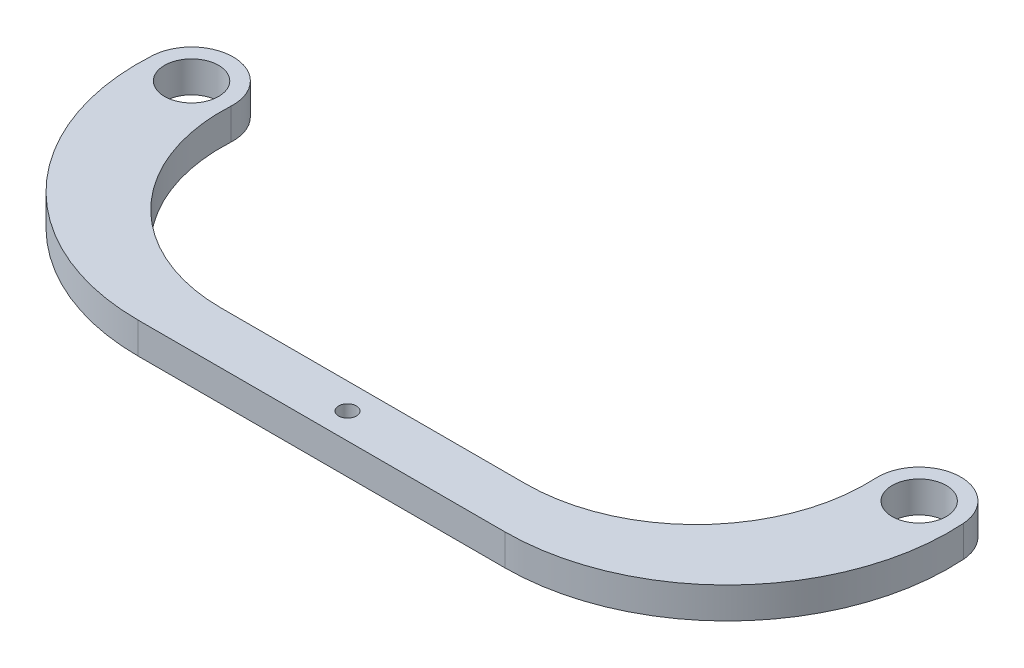
SolidWorks part; units mm, degrees
ref_plane "前视基准面" through (0, 0, 0) normal (0, 0, 1) x (1, 0, 0)
ref_plane "上视基准面" through (0, 0, 0) normal (0, 1, 0) x (1, 0, 0)
ref_plane "右视基准面" through (0, 0, 0) normal (1, 0, 0) x (0, 0, -1)
other "Configuration Table"
sketch "草图1" plane through (0, 0, 0) normal (0, 1, 0) x (1, 0, 0)
  line L0 (14.6414, 2.5) -> (-14.6414, 2.5)
  line L2 (17.6466, -2.5) -> (-17.6466, -2.5)
  circle A2 centre (35, 20) radius 2.6
  circle A3 centre (-35, 20) radius 2.6
  circle A4 centre (0, 0) radius 0.85
  arc A5 (38.9918, 20.2556) -> (31.0059, 19.782) centre (35, 20) ccw
  arc A6 (-31.0059, 19.782) -> (-38.9918, 20.2556) centre (-35, 20) ccw
  arc A7 (14.6414, 2.5) -> (31.0059, 19.782) centre (14.6414, 18.8889) ccw
  arc A9 (-31.0059, 19.782) -> (-14.6414, 2.5) centre (-14.6414, 18.8889) ccw
  arc A11 (-38.9918, 20.2556) -> (-17.6466, -2.5) centre (-17.6466, 18.8889) ccw
  arc A12 (17.6466, -2.5) -> (38.9918, 20.2556) centre (17.6466, 18.8889) ccw
  point P0 (0, 0)
  point P4 (0, -2.5)
  dimension "D4" = 5.2
  dimension "D5" = 5.2
  dimension "D6" = 1.7
  dimension "D7" = 8
  dimension "D8" = 8
  dimension "D9" = 5
  dimension "D10" = 2.5
  dimension "D11" = 16.3889
  dimension "D1" = 70
  dimension "D2" = 35
  dimension "D3" = 20
extrude "凸台-拉伸1" add sketch "草图1" along normal blind 3
